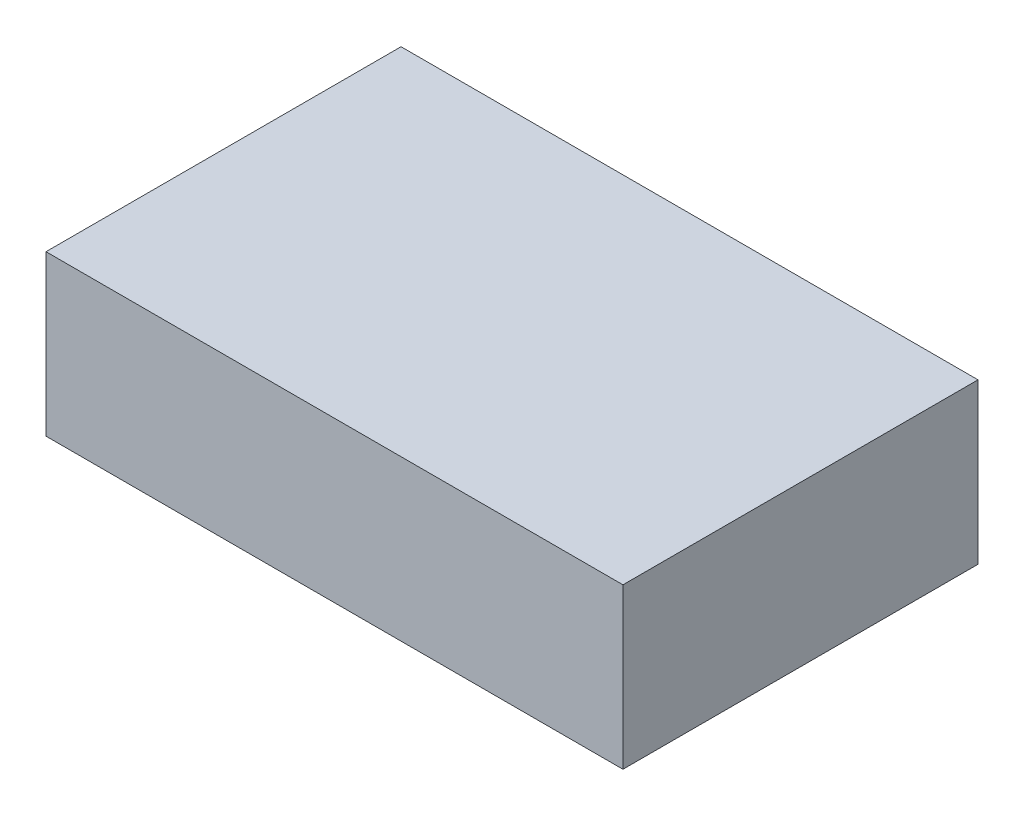
SolidWorks part; units mm, degrees
material "Custom Plastic"
ref_plane "Front Plane" through (0, 0, 0) normal (0, 0, 1) x (1, 0, 0)
ref_plane "Top Plane" through (0, 0, 0) normal (0, 1, 0) x (1, 0, 0)
ref_plane "Right Plane" through (0, 0, 0) normal (1, 0, 0) x (0, 0, -1)
sketch "Sketch1" plane through (0, 0, 0) normal (0, 1, 0) x (1, 0, 0)
  line L1 (0, 0) -> (82.55, 0)
  line L2 (0, 0) -> (0, 50.8)
  line L3 (0, 50.8) -> (82.55, 50.8)
  line L4 (82.55, 0) -> (82.55, 50.8)
  dimension "D1" = 82.55
  dimension "D2" = 50.8
extrude "Boss-Extrude1" add sketch "Sketch1" along normal blind 22.86
